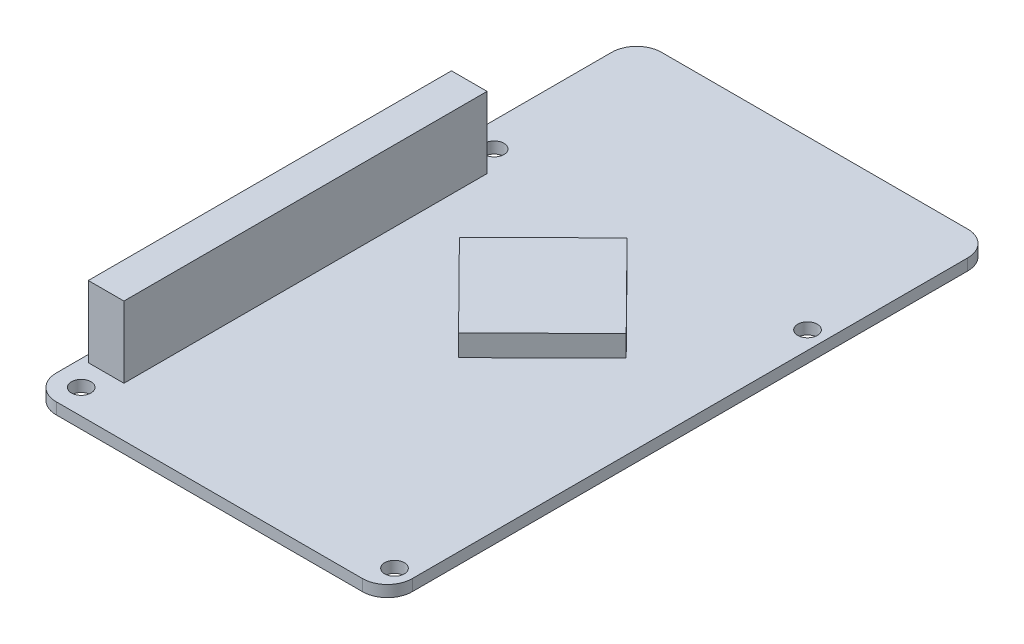
SolidWorks part; units mm, degrees
ref_plane "Front Plane" through (0, 0, 0) normal (0, 0, 1) x (1, 0, 0)
ref_plane "Top Plane" through (0, 0, 0) normal (0, 1, 0) x (1, 0, 0)
ref_plane "Right Plane" through (0, 0, 0) normal (1, 0, 0) x (0, 0, -1)
sketch "Sketch1" plane through (0, 0, 0) normal (0, 1, 0) x (1, 0, 0)
  line L1 (0, 0) -> (50, 0)
  line L2 (0, 0) -> (0, 85)
  line L3 (0, 85) -> (50, 85)
  line L4 (50, 0) -> (50, 85)
  circle A0 centre (3.5, 3.5) radius 1.375
  circle A1 centre (47.5, 3.5) radius 1.375
  circle A2 centre (47.5, 61.5) radius 1.375
  circle A3 centre (3.5, 61.5) radius 1.375
  point P13 (0, 0)
extrude "Boss-Extrude1" add sketch "Sketch1" along normal blind 1.6
fillet "Fillet1" radius 3.5 4 edges at (50, 0.8, -85) (0, 0.8, -85) (0, 0.8, 0) (50, 0.8, 0)
sketch "Sketch5" plane through (0, 1.6, 0) normal (0, 1, 0) x (1, 0, 0)
  line L1 (1, 7) -> (6, 7)
  line L2 (1, 7) -> (1, 58)
  line L3 (1, 58) -> (6, 58)
  line L4 (6, 7) -> (6, 58)
  line L5 (1, 7) -> (6, 58) construction
  line L6 (1, 58) -> (6, 7) construction
  point P0 (3.5, 32.5)
extrude "Boss-Extrude3" add sketch "Sketch5" along normal blind 10
sketch "Sketch6" plane through (0, 1.6, 0) normal (0, 1, 0) x (1, 0, 0)
  line L0 (26.6484, 57.0062) -> (38.2141, 45.3224)
  line L1 (26.6484, 57.0062) -> (14.8181, 45.2954)
  line L2 (38.2141, 45.3224) -> (26.3838, 33.6116)
  line L3 (14.8181, 45.2954) -> (26.3838, 33.6116)
extrude "Boss-Extrude4" add sketch "Sketch6" along normal blind 3 contours L0 L1 L3 L2
